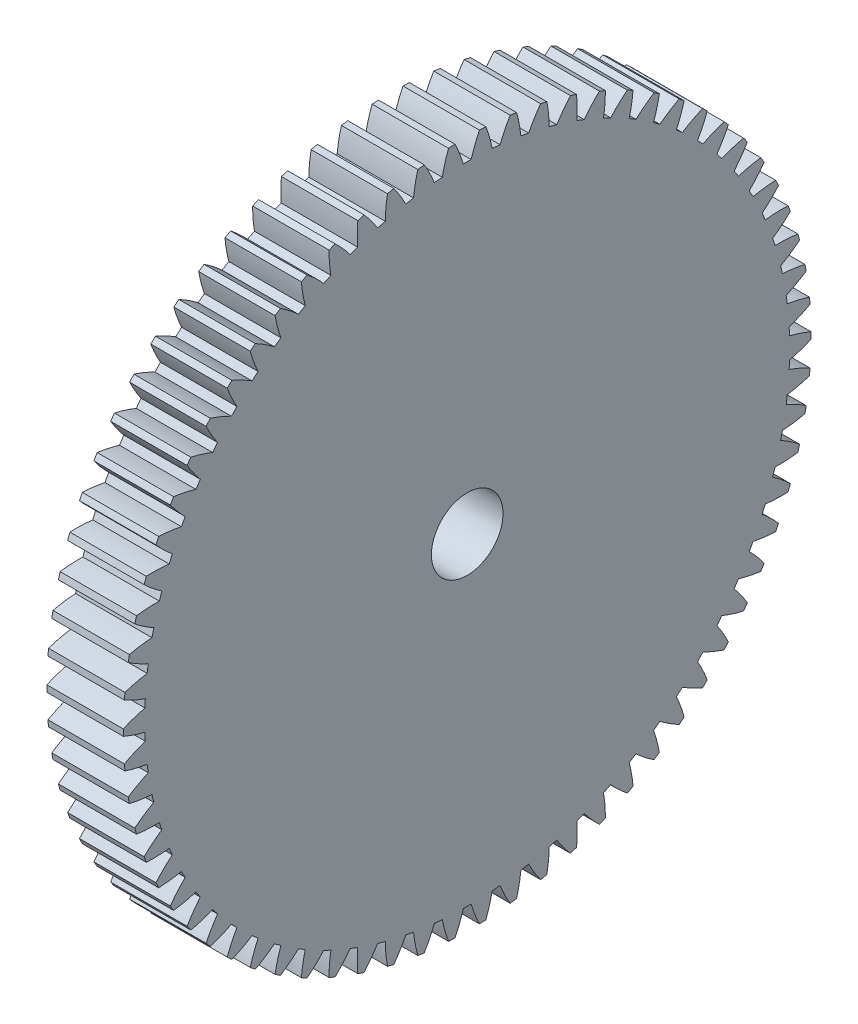
SolidWorks part; units mm, degrees
ref_plane "Plane1" through (0, 0, 0) normal (0, 0, 1) x (1, 0, 0)
ref_plane "Plane2" through (0, 0, 0) normal (0, 1, 0) x (1, 0, 0)
ref_plane "Plane3" through (0, 0, 0) normal (1, 0, 0) x (0, 0, -1)
sketch "HoldingSke" plane through (0, 0, 0) normal (0, 1, 0) x (1, 0, 0)
  line L0 (0, 0) -> (0.0855, -0.2349)
  line L1 (-15, 0) -> (100, 0) construction
  line L2 (0, 0) -> (-2.1039, 2.3779)
  line L3 (0, 0) -> (-11.863, 4.5341)
  line L4 (0, 0) -> (2.9537, 8.1152)
  line L5 (0, 0) -> (-46.8476, -17.4728)
  line L6 (0, 0) -> (-20.7241, -13.9826)
  line L7 (-2.1039, 2.3779) -> (8.6586, 51.2059)
  line L8 (-76.2, 54.61) -> (-72.9, 54.61)
  line L9 (-71.009, 38.7566) -> (-53.1078, 45.2721)
  line L10 (-76.2, 71.12) -> (104.1128, 71.12)
  line L11 (0, 0) -> (-25, 0)
  line L12 (-76.2, 101.6) -> (-76.073, 101.6)
  line L13 (24.9733, 27.94) -> (52.9518, 28.4284)
  line L14 (24.9733, 27.94) -> (24.9743, 27.94)
  line L15 (24.9733, 27.94) -> (100.4006, 29.5858)
  line L16 (-63.627, -4) -> (-12.827, -4)
  circle A0 centre (0, 0) radius 15
  circle A1 centre (0, 0) radius 37.5
  circle A2 centre (0, 0) radius 37.5
  circle A3 centre (0, 0) radius 15
  dimension "MHD" = 75
  dimension "Hub_dia" = 75
  dimension "Bore" = 30
  dimension "MBD" = 30
  dimension "Num_teeth" = 70
  dimension "Pitch" = 0.25
  dimension "Overall_len" = 50
  dimension "Show_teeth" = 70
  dimension "Thickness" = 25
  dimension "OAL" = 50.0001
  dimension "T_dim" = 3.3
  dimension "Ap" = 20
  dimension "H" = 19.05
  dimension "Pitch_radius" = 180.3128
  dimension "Width" = 25
  dimension "Backlash" = 0.127
  dimension "Addendum_fac" = 1
  dimension "Dedendum_fac" = 1.25
  dimension "Clearance_fac" = 0.25
  dimension "Dedendum_add" = 0.001
  dimension "Module" = 4
sketch "BasProSke" plane through (0, 0, 0) normal (0, 1, 0) x (1, 0, 0)
  line L0 (-10, 0) -> (60, 0) construction
  line L1 (0, 0) -> (0, 144)
  line L2 (0, 0) -> (32, 0)
  line L3 (32, 0) -> (32, 144)
  line L4 (32, 144) -> (0, 144)
  dimension "Thickness" = 32
  dimension "Diameter" = 288
revolve "Base-Revolve" add sketch "BasProSke" angle 360 about L0
sketch "TooCutSke" plane through (0, 0, 0) normal (1, 0, 0) x (0, 0, -1)
  line L1 (0, 0) -> (0, 107) construction
  line L2 (0, 0) -> (-3.3636, 139.9596) construction
  line L3 (0, 0) -> (-12.5594, 279.6572) construction
  line L4 (-3.3636, 139.9596) -> (-6.2797, 139.8286) construction
  arc A0 (1.6575, 134.9888) -> (-1.6575, 134.9888) centre (0, 0) ccw
  arc A1 (5.1214, 143.9343) -> (-5.1214, 143.9343) centre (0, 0) ccw
  circle A2 centre (0, 0) radius 140 construction
  circle A3 centre (0, 0) radius 131.557 construction
  arc A4 (-1.6575, 134.9888) -> (-5.1214, 143.9343) centre (-55.4191, 119.3145) ccw
  arc A5 (5.1214, 143.9343) -> (1.6575, 134.9888) centre (55.4191, 119.3145) ccw
  dimension "Root_dia" = 269.998
  dimension "Overcut_dia" = 288.0508
  dimension "Pitch_dia" = 280
  dimension "Base_dia" = 263.1139
  dimension "Flank_rad" = 56
  dimension "Half_ang" = 2.571
  dimension "Half_CT" = 2.9191
extrude "ToothCut" cut sketch "TooCutSke" along normal through all
fillet "Breaks" [suppressed] radius 0.08
fillet "RootFillets" [suppressed] radius 1.001
pattern_circular "TeethCuts" count 70 every 5.143 about axis through (-10, 0, 0) along (1, 0, 0) of "ToothCut", "RootFillets", "Breaks"
sketch "HubNeaOneSke" plane through (0, 0, 0) normal (-1, 0, 0) x (0, 0, 1)
  circle A0 centre (0, 0) radius 37.5
  dimension "Diameter" = 75
extrude "HubNearOne" [suppressed] add sketch "HubNeaOneSke" along normal blind 18.0001
sketch "HubNeaBotSke" plane through (0, 0, 0) normal (-1, 0, 0) x (0, 0, 1)
  circle A0 centre (0, 0) radius 37.5
  dimension "Diameter" = 75
extrude "HubNearBoth" [suppressed] add sketch "HubNeaBotSke" along normal blind 9
ref_plane "FarPln" through (32, 0, 0) normal (1, 0, 0) x (0, 0, -1)
sketch "HubFarSke" plane through (32, 0, 0) normal (1, 0, 0) x (0, 0, -1)
  circle A0 centre (0, 0) radius 37.5
  dimension "Diameter" = 75
extrude "HubFar" [suppressed] add sketch "HubFarSke" along normal blind 9
sketch "BorSke" plane through (0, 0, 0) normal (1, 0, 0) x (0, 0, -1)
  circle A0 centre (0, 0) radius 15
  dimension "Diameter" = 30
extrude "Bore" cut sketch "BorSke" along normal mid plane 100.0001
sketch "KeySke" plane through (0, 0, 0) normal (1, 0, 0) x (0, 0, -1)
  line L0 (-4, 0) -> (-4, 18.3)
  line L1 (-4, 18.3) -> (4, 18.3)
  line L2 (4, 18.3) -> (4, 0)
  line L3 (0, 0) -> (0, 34) construction
  line L4 (-4, 0) -> (4, 0)
  dimension "Offset" = 18.3
  dimension "Width" = 8
extrude "Keyway" [suppressed] cut sketch "KeySke" along normal mid plane 100.0001
pattern_circular "Keyway2" [suppressed] count 2 every 90 about axis through (-10, 0, 0) along (1, 0, 0)
equation "' \"Module@HoldingSke\" = 6.35"
equation "' \"Num_teeth@HoldingSke\" = 12"
equation "' \"Ap@HoldingSke\" =  20"
equation "' \"Ap@HoldingSke\" = 20"
equation "' \"Width@HoldingSke\" = 0.5 * 25.4"
equation "' \"Hub_dia@HoldingSke\"= 1 * 25.4"
equation "' \"Hub_dia@HoldingSke\" = 1 * 25.4"
equation "' \"Overall_len@HoldingSke\" = 1.0 * 25.4"
equation "' \"Bore@HoldingSke\" = 0.75 * 25.4"
equation "' \"T_dim@HoldingSke\" = 0.1 * 25.4"
equation "' \"Width@KeySke\" = 0.25 * 25.4"
equation "' \"Show_teeth@HoldingSke\" = 13"
equation "' \"Backlash@HoldingSke\" = 0.009 * 25.4"
equation "' \"Addendum_fac@HoldingSke\" = 1.0"
equation "' \"Dedendum_fac@HoldingSke\" = 1.25"
equation "' \"Dedendum_add@HoldingSke\" = 0.00005 * 25.4"
equation "' \"Clearance_fac@HoldingSke\" = 0.25"
equation "\"Pitch@HoldingSke\" = 1 / \"Module@HoldingSke\""
equation "\"Overcut_dia@TooCutSke\" = (\"Num_teeth@HoldingSke\" + 2 * \"Addendum_fac@HoldingSke\") / \"Pitch@HoldingSke\" + 0.002 * 25.4"
equation "\"Pitch_dia@TooCutSke\" = \"Num_teeth@HoldingSke\" / \"Pitch@HoldingSke\""
equation "\"Base_dia@TooCutSke\" = \"Num_teeth@HoldingSke\" / \"Pitch@HoldingSke\" * cos((\"Ap@HoldingSke\"  * 3.14159265 / 180))"
equation "\"Root_dia@TooCutSke\" = (\"Num_teeth@HoldingSke\" + 2) / \"Pitch@HoldingSke\" - 2 * (\"Addendum_fac@HoldingSke\" + \"Dedendum_fac@HoldingSke\") / \"Pitch@HoldingSke\" - \"Dedendum_add@HoldingSke\" * 2"
equation "\"Half_ang@TooCutSke\" = 180 / \"Num_teeth@HoldingSke\""
equation "\"Half_CT@TooCutSke\" = \"Num_teeth@HoldingSke\" / \"Pitch@HoldingSke\" * sin((3.14159265 / 2 / \"Num_teeth@HoldingSke\")) / 2 - 7 * \"Backlash@HoldingSke\" / 4"
equation "\"Flank_rad@TooCutSke\" = \"Num_teeth@HoldingSke\" / \"Pitch@HoldingSke\" / 5"
equation "\"Radius@RootFillets\" = \"Clearance_fac@HoldingSke\" / \"Pitch@HoldingSke\" + \"Dedendum_add@HoldingSke\""
equation "\"Break_rad@Breaks\" = 0.02 / \"Pitch@HoldingSke\""
equation "\"Thickness@HoldingSke\" = \"Width@HoldingSke\""
equation "\"OAL@HoldingSke\" = \"Thickness@HoldingSke\""
equation "\"MHD@HoldingSke\" = (\"Num_teeth@HoldingSke\" + 2) / \"Pitch@HoldingSke\" - 2 * (\"Addendum_fac@HoldingSke\" + \"Dedendum_fac@HoldingSke\")  / \"Pitch@HoldingSke\" - \"Dedendum_add@HoldingSke\" * 2"
equation "\"MBD@HoldingSke\" = (\"Num_teeth@HoldingSke\" + 2) / \"Pitch@HoldingSke\" - 2 * (\"Addendum_fac@HoldingSke\" + \"Dedendum_fac@HoldingSke\")  / \"Pitch@HoldingSke\" - \"Dedendum_add@HoldingSke\" * 2 - 0.002 * 25.4"
equation "\"MHD@HoldingSke\" = ((sgn( \"MHD@HoldingSke\" - \"Hub_dia@HoldingSke\" )-1)*( \"MHD@HoldingSke\" - \"Hub_dia@HoldingSke\" ))/-2+ \"Hub_dia@HoldingSke\""
equation "\"MBD@HoldingSke\" = ((sgn( \"MBD@HoldingSke\" - \"Bore@HoldingSke\" )-1)*( \"MBD@HoldingSke\" - \"Bore@HoldingSke\" ))/-2+ \"Bore@HoldingSke\""
equation "\"OAL@HoldingSke\" = ((sgn( \"OAL@HoldingSke\" - \"Overall_len@HoldingSke\" )+1)*( \"OAL@HoldingSke\" - \"Overall_len@HoldingSke\" ))/2 + \"Overall_len@HoldingSke\" + 0.000002 * 25.4"
equation "\"Num_teeth@TeethCuts\" = int( \"Show_teeth@HoldingSke\" ) + 1"
equation "\"Num_teeth@TeethCuts\" = ((sgn( \"Num_teeth@TeethCuts\" - \"Num_teeth@HoldingSke\" )-1)*( \"Num_teeth@TeethCuts\" - \"Num_teeth@HoldingSke\" ))/-2+ \"Num_teeth@HoldingSke\""
equation "\"Num_teeth@TeethCuts\" = ((sgn( \"Num_teeth@TeethCuts\" - 2.0)+1)*( \"Num_teeth@TeethCuts\" - 2.0))/2 +2.0"
equation "\"Angle@TeethCuts\" = 360.0 / \"Num_teeth@HoldingSke\""
equation "\"Diameter@BasProSke\" = (\"Num_teeth@HoldingSke\" + 2 * \"Addendum_fac@HoldingSke\") / \"Pitch@HoldingSke\""
equation "\"Thickness@BasProSke\"=\"Thickness@HoldingSke\"+7"
equation "' \"Fillet_rad@BasProSke\" =  \"Thickness@HoldingSke\" * 0.05"
equation "' \"Fillet_rad@BasProSke\" = \"Thickness@HoldingSke\" * 0.05"
equation "\"MHD@HoldingSke\" = ((sgn( \"MHD@HoldingSke\" - \"Root_dia@TooCutSke\" )-1)*( \"MHD@HoldingSke\" - \"Root_dia@TooCutSke\" ))/-2+ \"Root_dia@TooCutSke\""
equation "\"Diameter@HubNeaOneSke\" = \"MHD@HoldingSke\""
equation "\"Length@HubNearOne\" = \"OAL@HoldingSke\" - \"Thickness@BasProSke\""
equation "\"Diameter@HubNeaBotSke\" = \"MHD@HoldingSke\""
equation "\"Length@HubNearBoth\" = ( \"OAL@HoldingSke\" - \"Thickness@BasProSke\" ) / 2.0"
equation "\"Thickness@FarPln\" = \"Thickness@BasProSke\""
equation "\"Diameter@HubFarSke\" = \"MHD@HoldingSke\""
equation "\"Length@HubFar\" = ( \"OAL@HoldingSke\" - \"Thickness@BasProSke\" ) / 2.0"
equation "\"Diameter@BorSke\" = \"MBD@HoldingSke\""
equation "\"D1@Bore\" = \"OAL@HoldingSke\" * 2.0"
equation "\"D1@Keyway\" = \"OAL@HoldingSke\" * 2.0"
equation "\"Offset@KeySke\" = \"T_dim@HoldingSke\" + \"MBD@HoldingSke\" / 2.0"
